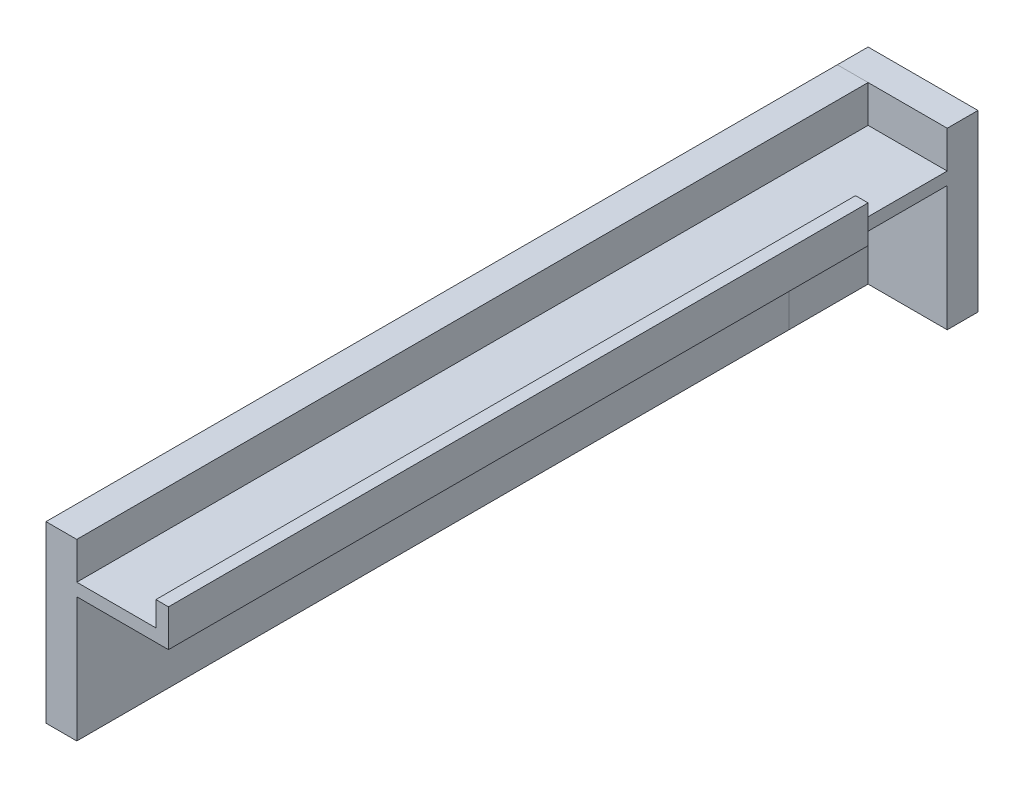
SolidWorks part; units mm, degrees
ref_plane "Front Plane" through (0, 0, 0) normal (0, 0, 1) x (1, 0, 0)
ref_plane "Top Plane" through (0, 0, 0) normal (0, 1, 0) x (1, 0, 0)
ref_plane "Right Plane" through (0, 0, 0) normal (1, 0, 0) x (0, 0, -1)
sketch "Sketch1" plane through (0, 0, 0) normal (0, 0, 1) x (1, 0, 0)
  line L0 (-44.446, 17.8924) -> (-44.446, -52.7221)
  line L1 (-44.446, -52.7221) -> (-31.996, -52.7221)
  line L2 (-31.996, -52.7221) -> (-31.996, -2.1876)
  line L3 (-31.996, -2.1876) -> (5.08, -2.1876)
  line L4 (5.08, -2.1876) -> (5.08, 12.8124)
  line L10 (0, 12.8124) -> (0, 2.8924)
  line L11 (0, 2.8924) -> (-32, 2.8924)
  line L12 (-32, 2.8924) -> (-32, 17.8924)
  line L13 (-32, 17.8924) -> (-44.446, 17.8924)
  line L14 (5.08, 12.8124) -> (0, 12.8124)
  dimension "D1" = 12.446
  dimension "D2" = 70.6145
  dimension "D3" = 32
  dimension "D4" = 12.45
  dimension "D5" = 5.08
  dimension "D6" = 15
  dimension "D7" = 9.92
extrude "Boss-Extrude1" add sketch "Sketch1" along normal blind 288.036
sketch "Sketch2" plane through (0, 12.8124, 0) normal (0, 1, 0) x (1, 0, 0)
  line L0 (5.08, -288.036) -> (5.08, 0) construction
  line L1 (0, 0) -> (5.08, 0)
  line L2 (0, 0) -> (0, -5.08)
  line L3 (0, -5.08) -> (5.08, -5.08)
  line L4 (5.08, 0) -> (5.08, -5.08)
  dimension "D1" = 5.08
extrude "Cut-Extrude1" cut sketch "Sketch2" against normal through all
sketch "Sketch3" plane through (0, 0, 0) normal (0, 0, -1) x (-1, 0, 0)
  line L1 (32, 17.8924) -> (44.446, 17.8924)
  line L2 (32, 17.8924) -> (32, -52.7221)
  line L3 (32, -52.7221) -> (44.446, -52.7221)
  line L4 (44.446, 17.8924) -> (44.446, -52.7221)
  line L5 (0, 2.8924) -> (31.996, 2.8924)
  line L6 (0, 2.8924) -> (0, -2.1876)
  line L7 (0, -2.1876) -> (31.996, -2.1876)
  line L8 (31.996, 2.8924) -> (31.996, -2.1876)
extrude "Boss-Extrude2" add sketch "Sketch3" along normal blind 32
sketch "Sketch7" plane through (0, 0, -32) normal (0, 0, -1) x (-1, 0, 0)
  line L1 (44.446, -52.7221) -> (0, -52.7221)
  line L2 (44.446, -52.7221) -> (44.446, 17.8879)
  line L3 (44.446, 17.8879) -> (0, 17.8879)
  line L4 (0, -52.7221) -> (0, 17.8879)
  dimension "D1" = 70.61
extrude "Boss-Extrude3" add sketch "Sketch7" along normal blind 12.45
